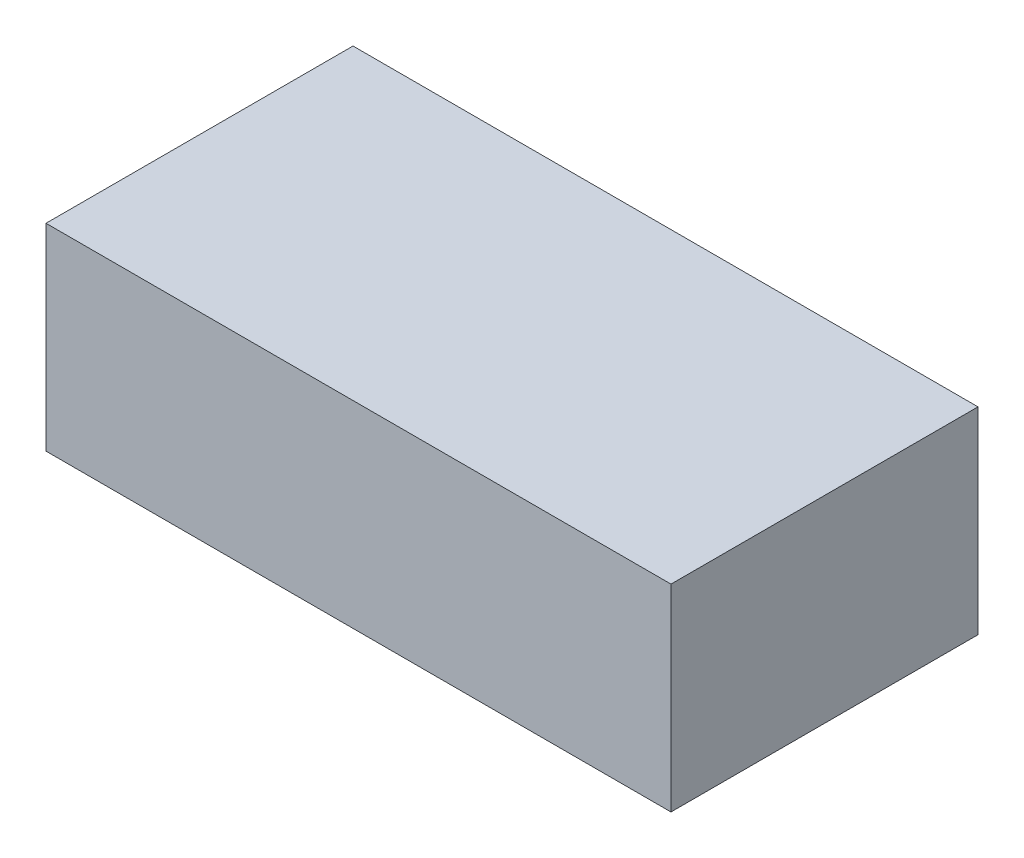
SolidWorks part; units mm, degrees
ref_plane "前视基准面" through (0, 0, 0) normal (0, 0, 1) x (1, 0, 0)
ref_plane "上视基准面" through (0, 0, 0) normal (0, 1, 0) x (1, 0, 0)
ref_plane "右视基准面" through (0, 0, 0) normal (1, 0, 0) x (0, 0, -1)
other "Configuration Table"
sketch "草图1" plane through (0, 0, 0) normal (0, 0, 1) x (1, 0, 0)
  line L0 (0, 0) -> (57, 0)
  line L1 (57, 0) -> (57, 18)
  line L2 (57, 18) -> (0, 18)
  line L3 (0, 18) -> (0, 0)
  dimension "width" = 57
  dimension "height" = 18
extrude "Side_arm" add sketch "草图1" along normal blind 28
